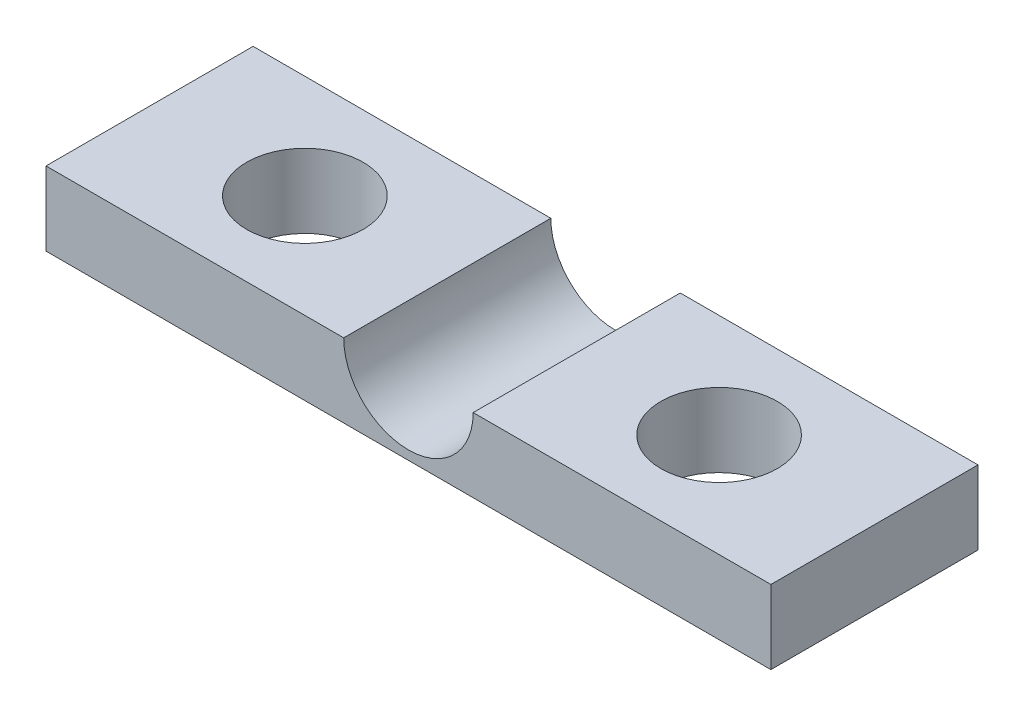
SolidWorks part; units mm, degrees
ref_plane "Front Plane" through (0, 0, 0) normal (0, 0, 1) x (1, 0, 0)
ref_plane "Top Plane" through (0, 0, 0) normal (0, 1, 0) x (1, 0, 0)
ref_plane "Right Plane" through (0, 0, 0) normal (1, 0, 0) x (0, 0, -1)
sketch "Sketch1" plane through (0, 0, 0) normal (0, 0, 1) x (1, 0, 0)
  line L0 (0, 0) -> (-28, 0)
  line L1 (-28, 0) -> (-28, 2.85)
  line L2 (-28, 2.85) -> (-16.5, 2.85)
  line L3 (0, 2.85) -> (0, 0)
  line L4 (-16.5, 2.85) -> (-11.5, 2.85) construction
  line L5 (-11.5, 2.85) -> (0, 2.85)
  arc A0 (-16.5, 2.85) -> (-11.5, 2.85) centre (-14, 2.85) ccw
  arc A1 (-11.5, 2.85) -> (-16.5, 2.85) centre (-14, 2.85) ccw construction
  point P11 (-14, 0)
  dimension "D2" = 5
  dimension "D1" = 28
  dimension "D3" = 2.85
extrude "Boss-Extrude1" add sketch "Sketch1" along normal blind 8
sketch "Sketch2" plane through (0, 2.85, 0) normal (0, 1, 0) x (1, 0, 0)
  line L0 (-14, -8) -> (-14, 0) construction
  line L1 (-16.5, -8) -> (-11.5, -8) construction
  line L2 (-11.5, 0) -> (-16.5, 0) construction
  line L3 (-16.5, -8) -> (-28, -8) construction
  circle A0 centre (-22, -4) radius 2.25
  circle A1 centre (-6, -4) radius 2.25
  dimension "D1" = 4.5
  dimension "D2" = 8
  dimension "D3" = 4
  dimension "D4" = 8
extrude "Cut-Extrude1" cut sketch "Sketch2" against normal up to next
